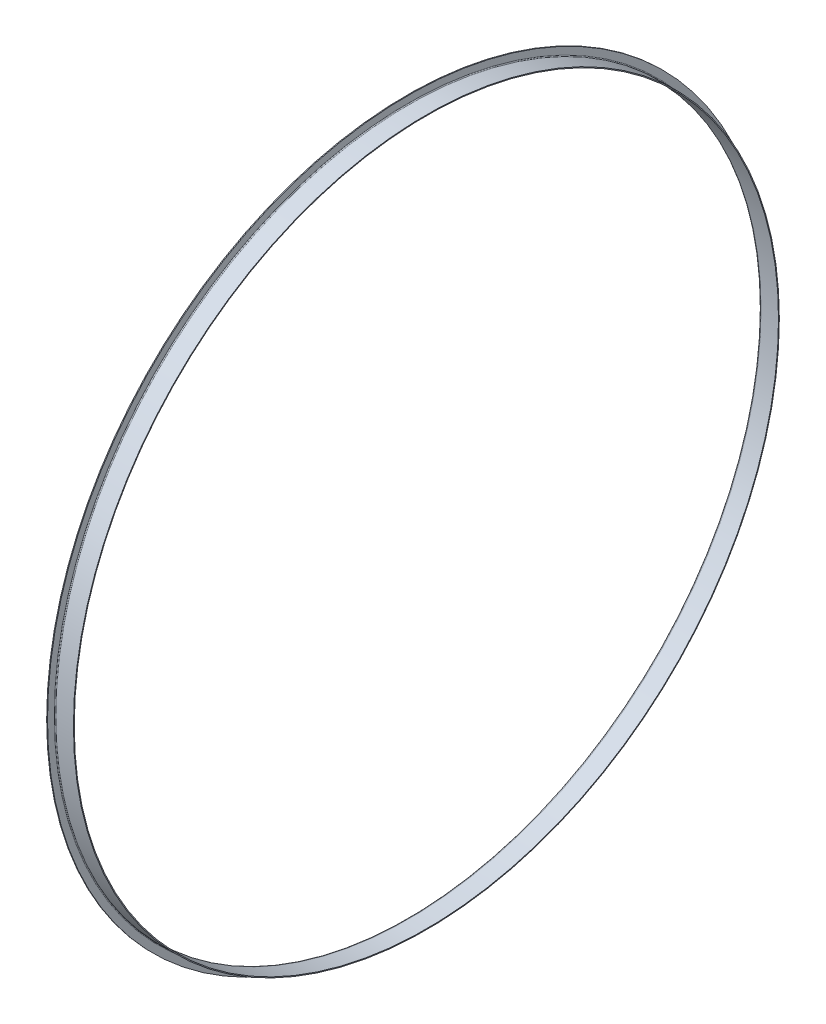
SolidWorks part; units mm, degrees
material "ASTM A36 Steel"
ref_plane "Front Plane" through (0, 0, 0) normal (0, 0, 1) x (1, 0, 0)
ref_plane "Top Plane" through (0, 0, 0) normal (0, 1, 0) x (1, 0, 0)
ref_plane "Right Plane" through (0, 0, 0) normal (1, 0, 0) x (0, 0, -1)
sketch "Sketch1" plane through (0, 0, 0) normal (0, 0, 1) x (1, 0, 0)
  line L0 (12.439, 115.4021) -> (-49.561, 115.4021)
  line L1 (-55.561, 121.4021) -> (-55.561, 145.4021)
  line L2 (-55.561, 145.4021) -> (-52.561, 145.4021)
  line L3 (-52.561, 145.4021) -> (-52.561, 121.4021)
  line L4 (-49.561, 118.4021) -> (12.439, 118.4021)
  line L5 (12.439, 118.4021) -> (12.439, 115.4021)
  line L6 (-55.561, -1134.5979) -> (240.8401, -1134.5979) construction
  arc A0 (-52.561, 121.4021) -> (-49.561, 118.4021) centre (-49.561, 121.4021) ccw
  arc A1 (-49.561, 115.4021) -> (-55.561, 121.4021) centre (-49.561, 121.4021) cw
  point P10 (-55.561, 115.4021)
  dimension "D5" = 3
  dimension "D6" = 6
  dimension "D1" = 68
  dimension "D2" = 30
  dimension "D3" = 3
  dimension "D4" = 3
  dimension "D7" = 1250
revolve "Revolve1" add sketch "Sketch1" angle 360 about L6
